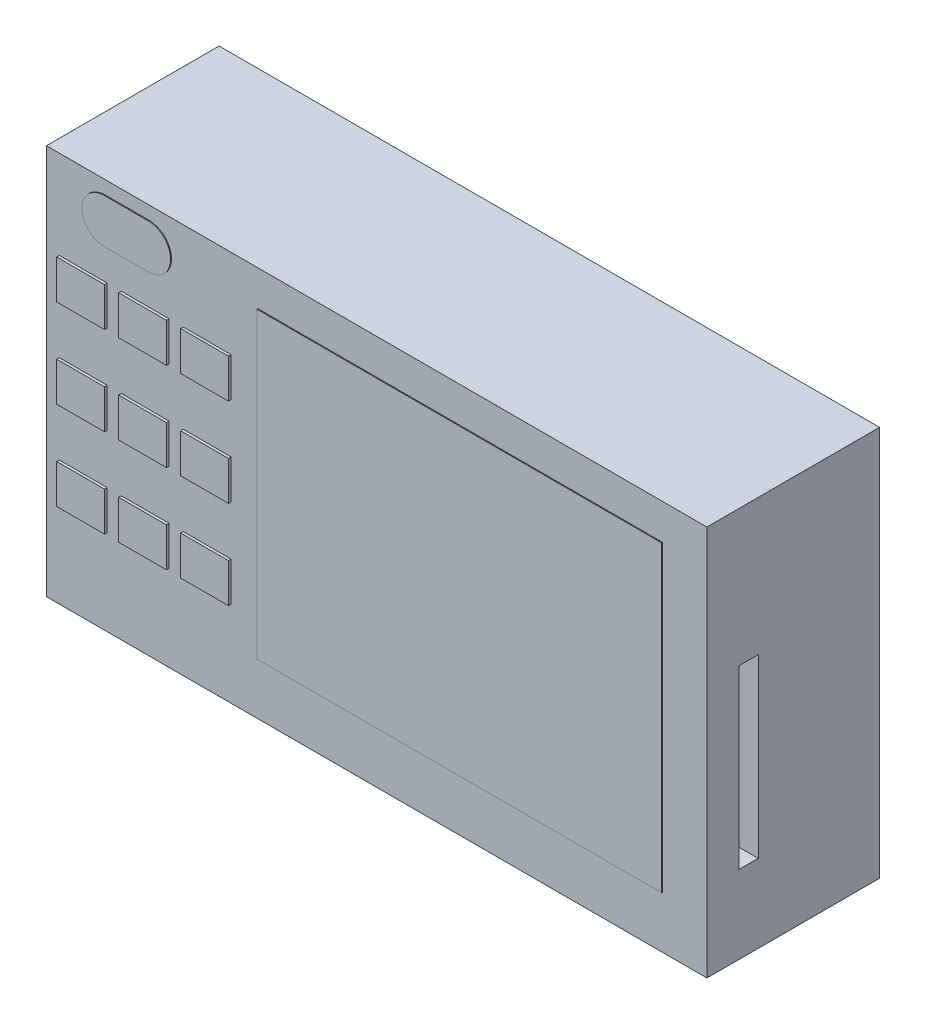
SolidWorks part; units mm, degrees
ref_plane "Front Plane" through (0, 0, 0) normal (0, 0, 1) x (1, 0, 0)
ref_plane "Top Plane" through (0, 0, 0) normal (0, 1, 0) x (1, 0, 0)
ref_plane "Right Plane" through (0, 0, 0) normal (1, 0, 0) x (0, 0, -1)
sketch "Sketch1" plane through (0, 0, 0) normal (0, 0, 1) x (1, 0, 0)
  line L1 (-47.3583, -28.0035) -> (47.3583, -28.0035)
  line L2 (-47.3583, -28.0035) -> (-47.3583, 28.0035)
  line L3 (-47.3583, 28.0035) -> (47.3583, 28.0035)
  line L4 (47.3583, -28.0035) -> (47.3583, 28.0035)
  line L5 (-47.3583, -28.0035) -> (47.3583, 28.0035) construction
  line L6 (-47.3583, 28.0035) -> (47.3583, -28.0035) construction
  point P0 (0, 0)
  dimension "D1" = 94.7166
  dimension "D2" = 56.007
extrude "Extrude1" add sketch "Sketch1" along normal blind 24.765
sketch "Sketch2" plane through (0, 0, 24.765) normal (0, 0, 1) x (1, 0, 0)
  line L0 (47.3583, 28.0035) -> (-47.3583, 28.0035) construction
  line L1 (-17.0561, 22.9235) -> (41.0083, 22.9235)
  line L2 (-17.0561, 22.9235) -> (-17.0561, -20.5359)
  line L3 (-17.0561, -20.5359) -> (41.0083, -20.5359)
  line L4 (41.0083, 22.9235) -> (41.0083, -20.5359)
  line L5 (-17.0561, 22.9235) -> (41.0083, -20.5359) construction
  line L6 (-17.0561, -20.5359) -> (41.0083, 22.9235) construction
  line L7 (47.3583, -28.0035) -> (47.3583, 28.0035) construction
  line L8 (-38.9504, 22.9235) -> (-32.6004, 22.9235) construction
  line L9 (-38.9504, 26.0985) -> (-32.6004, 26.0985)
  line L10 (-38.9504, 19.7485) -> (-32.6004, 19.7485)
  arc A0 (-38.9504, 26.0985) -> (-38.9504, 19.7485) centre (-38.9504, 22.9235) ccw
  arc A1 (-32.6004, 19.7485) -> (-32.6004, 26.0985) centre (-32.6004, 22.9235) ccw
  point P0 (11.9761, 1.1938)
  point P11 (-35.7754, 22.9235)
  dimension "D6" = 6.35
  dimension "D1" = 58.0644
  dimension "D2" = 43.4594
  dimension "D3" = 5.08
  dimension "D4" = 6.35
  dimension "D5" = 6.35
extrude "Extrude2" add sketch "Sketch2" along normal blind 0.127
sketch "Sketch3" plane through (0, 0, 24.765) normal (0, 0, 1) x (1, 0, 0)
  line L0 (-17.0561, 22.9235) -> (-17.0561, -20.5359) construction
  line L1 (-27.7241, 15.3035) -> (-20.8661, 15.3035)
  line L2 (-27.7241, 15.3035) -> (-27.7241, 9.7155)
  line L3 (-27.7241, 9.7155) -> (-20.8661, 9.7155)
  line L4 (-20.8661, 15.3035) -> (-20.8661, 9.7155)
  line L5 (-27.7241, 15.3035) -> (-20.8661, 9.7155) construction
  line L6 (-27.7241, 9.7155) -> (-20.8661, 15.3035) construction
  line L7 (47.3583, 28.0035) -> (-47.3583, 28.0035) construction
  point P0 (-24.2951, 12.5095)
  dimension "D1" = 6.858
  dimension "D2" = 5.588
  dimension "D3" = 3.81
  dimension "D4" = 12.7
extrude "Extrude3" add sketch "Sketch3" along normal blind 0.381
pattern_linear "LPattern1" count 3 spacing 8.89 along (-1, 0, 0) of "Extrude3"
pattern_linear "LPattern2" count 3 spacing 12.7 along (0, -1, 0) of "LPattern1", "Extrude3"
sketch "Sketch4" plane through (-47.3583, 0, 0) normal (-1, 0, 0) x (0, 0, 1)
  line L0 (0, 28.0035) -> (0, -28.0035) construction
  line L1 (23.904, 17.8435) -> (18.951, 17.8435)
  line L2 (23.904, 17.8435) -> (23.904, 1.3335)
  line L3 (23.904, 1.3335) -> (18.951, 1.3335)
  line L4 (18.951, 17.8435) -> (18.951, 1.3335)
  line L5 (23.904, 17.8435) -> (18.951, 1.3335) construction
  line L6 (23.904, 1.3335) -> (18.951, 17.8435) construction
  line L7 (14.732, 21.7805) -> (7.112, 21.7805)
  line L8 (14.732, 21.7805) -> (14.732, 0.1905)
  line L9 (14.732, 0.1905) -> (7.112, 0.1905)
  line L10 (7.112, 21.7805) -> (7.112, 0.1905)
  line L11 (14.732, 21.7805) -> (7.112, 0.1905) construction
  line L12 (14.732, 0.1905) -> (7.112, 21.7805) construction
  line L13 (24.765, -28.0035) -> (0, -28.0035) construction
  line L14 (24.765, 28.0035) -> (0, 28.0035) construction
  line L15 (24.765, 28.0035) -> (24.765, -28.0035) construction
  circle A0 centre (12.192, -6.4135) radius 1.524
  circle A1 centre (12.192, -16.3195) radius 2.54
  point P0 (21.4275, 9.5885)
  point P9 (10.922, 10.9855)
  dimension "D1" = 5.08
  dimension "D2" = 3.048
  dimension "D3" = 12.192
  dimension "D4" = 12.192
  dimension "D5" = 11.684
  dimension "D6" = 21.59
  dimension "D7" = 28.194
  dimension "D8" = 21.59
  dimension "D9" = 7.62
  dimension "D10" = 7.112
  dimension "D11" = 4.953
  dimension "D12" = 16.51
  dimension "D13" = 10.16
  dimension "D14" = 0.861
extrude "Extrude4" add sketch "Sketch4" along normal blind 0.381
sketch "Sketch5" plane through (0, -28.0035, 0) normal (0, -1, 0) x (1, 0, 0)
  line L0 (-47.3583, 24.765) -> (-47.3583, 0) construction
  line L1 (-32.1183, 16.383) -> (-16.8783, 16.383)
  line L2 (-32.1183, 16.383) -> (-32.1183, 11.811)
  line L3 (-32.1183, 11.811) -> (-16.8783, 11.811)
  line L4 (-16.8783, 16.383) -> (-16.8783, 11.811)
  line L5 (-1.6383, 16.383) -> (11.0617, 16.383)
  line L6 (-1.6383, 16.383) -> (-1.6383, 11.811)
  line L7 (-1.6383, 11.811) -> (11.0617, 11.811)
  line L8 (11.0617, 16.383) -> (11.0617, 11.811)
  line L9 (12.8397, 16.383) -> (38.2397, 16.383)
  line L10 (12.8397, 16.383) -> (12.8397, 9.779)
  line L11 (12.8397, 9.779) -> (38.2397, 9.779)
  line L12 (38.2397, 16.383) -> (38.2397, 9.779)
  line L13 (-47.3583, 24.765) -> (47.3583, 24.765) construction
  circle A0 centre (-9.2583, 14.351) radius 2.286
  dimension "D1" = 4.572
  dimension "D7" = 38.1
  dimension "D2" = 15.24
  dimension "D3" = 12.7
  dimension "D4" = 4.572
  dimension "D5" = 4.572
  dimension "D6" = 15.24
  dimension "D8" = 45.72
  dimension "D9" = 60.198
  dimension "D10" = 25.4
  dimension "D11" = 6.604
  dimension "D12" = 8.382
  dimension "D13" = 10.414
extrude "Extrude5" add sketch "Sketch5" along normal blind 0.381
sketch "Sketch6" plane through (47.3583, 0, 0) normal (1, 0, 0) x (0, 0, -1)
  line L0 (-24.765, -28.0035) -> (0, -28.0035) construction
  line L1 (-20.193, -16.8275) -> (-17.399, -16.8275)
  line L2 (-20.193, -16.8275) -> (-20.193, 8.4709)
  line L3 (-20.193, 8.4709) -> (-17.399, 8.4709)
  line L4 (-17.399, -16.8275) -> (-17.399, 8.4709)
  line L5 (-24.765, -28.0035) -> (-24.765, 28.0035) construction
  dimension "D1" = 25.2984
  dimension "D2" = 2.794
  dimension "D3" = 11.176
  dimension "D4" = 4.572
extrude "Extrude6" cut sketch "Sketch6" against normal blind 28.321
